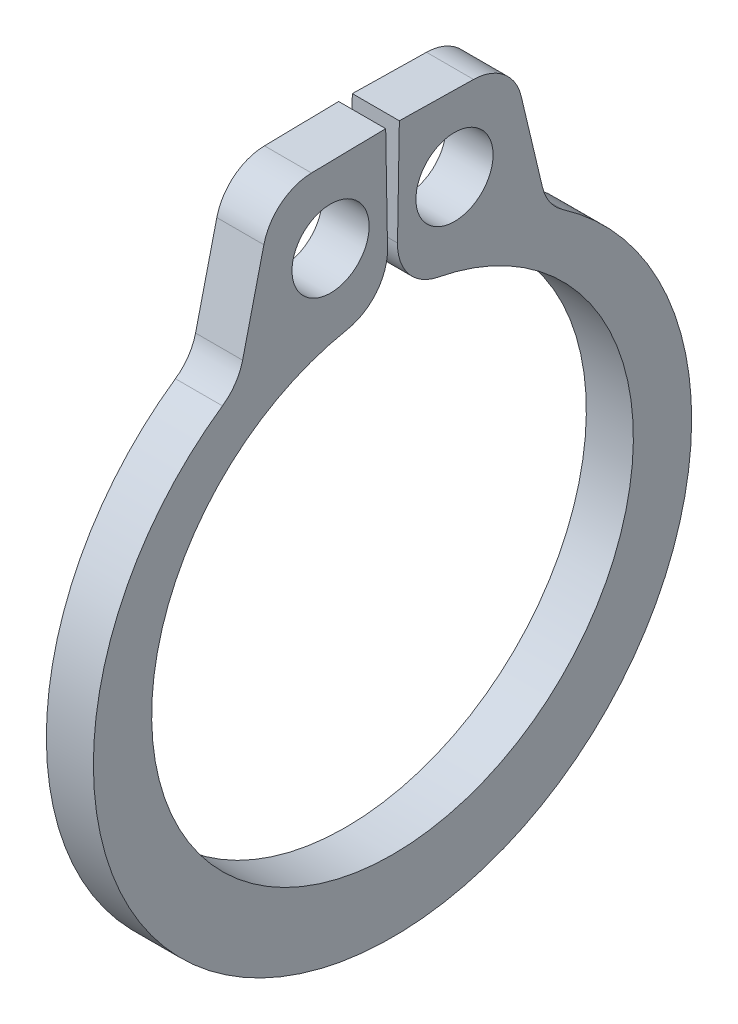
SolidWorks part; units mm, degrees
material "Cast Carbon Steel"
ref_plane "Front" through (0, 0, 0) normal (0, 0, 1) x (1, 0, 0)
ref_plane "Top" through (0, 0, 0) normal (0, 1, 0) x (1, 0, 0)
ref_plane "Right" through (0, 0, 0) normal (1, 0, 0) x (0, 0, -1)
sketch "Sketch1" plane through (0, 0, 0) normal (1, 0, 0) x (0, 0, -1)
  line L0 (0, 0) -> (0, 3.2512) construction
  line L1 (-0.0567, 3.2507) -> (-0.0922, 5.2824)
  line L2 (0.0922, 5.2824) -> (1.616, 5.2558)
  line L3 (1.616, 5.2558) -> (2.086, 3.2789)
  line L4 (0.0567, 3.2507) -> (0.0922, 5.2824)
  line L5 (-0.0922, 5.2824) -> (-1.616, 5.2558)
  line L6 (-1.616, 5.2558) -> (-2.086, 3.2789)
  line L7 (-2.086, 3.2789) -> (-1.7451, 2.7431) construction
  line L8 (2.086, 3.2789) -> (1.7451, 2.7431) construction
  line L9 (0, -3.2512) -> (0, -4.2164) construction
  line L10 (-1.616, 5.2558) -> (-0.0567, 3.2507) construction
  line L11 (0, 3.2512) -> (0, 5.2832) construction
  line L12 (-3.2512, 0) -> (3.2512, 0) construction
  circle A0 centre (0, 0) radius 3.2512 construction
  arc A1 (-0.0567, 3.2507) -> (0.0567, 3.2507) centre (0, 0) ccw
  circle A4 centre (-0.8364, 4.2533) radius 0.5207
  circle A5 centre (0.8364, 4.2533) radius 0.5207
  arc A6 (-2.086, 3.2789) -> (2.086, 3.2789) centre (0, -0.1785) ccw construction
  point P0 (0, -4.2164)
  dimension "Ring ID" = 6.5024
  dimension "Hole Diameter" = 1.0414
  dimension "Min. Sec." = 0.635
  dimension "Max. Sec." = 0.9652
  dimension "Lug Height" = 2.032
  dimension "D2" = 1.524
  dimension "Angle" = 1
sketch "Sketch2" plane through (0, 0, 0) normal (0, 1, 0) x (1, 0, 0)
  line L0 (-0.3175, -4.034) -> (0.3175, -4.034) construction
  line L1 (0, -4.0379) -> (0, 4.0379) construction
  point P8 (0, -4.034)
  dimension "Ring Thickness" = 0.635
sketch "Sketch3" plane through (0, 0, 0) normal (1, 0, 0) x (0, 0, -1)
  line L0 (-1.616, 5.2558) -> (-2.086, 3.2789) construction
  line L1 (-1.616, 5.2558) -> (-2.086, 3.2789)
  line L2 (-0.0922, 5.2824) -> (-1.616, 5.2558) construction
  line L3 (-0.0922, 5.2824) -> (-1.616, 5.2558)
  line L4 (-0.0567, 3.2507) -> (-0.0922, 5.2824) construction
  line L5 (-0.0567, 3.2507) -> (-0.0922, 5.2824)
  line L6 (0.0567, 3.2507) -> (0.0922, 5.2824) construction
  line L7 (0.0567, 3.2507) -> (0.0922, 5.2824)
  line L8 (0.0922, 5.2824) -> (1.616, 5.2558) construction
  line L9 (0.0922, 5.2824) -> (1.616, 5.2558)
  line L10 (1.616, 5.2558) -> (2.086, 3.2789) construction
  line L11 (1.616, 5.2558) -> (2.086, 3.2789)
  arc A0 (-2.086, 3.2789) -> (2.086, 3.2789) centre (0, -0.1785) ccw construction
  arc A1 (-2.086, 3.2789) -> (2.086, 3.2789) centre (0, -0.1785) ccw
  arc A2 (-0.0567, 3.2507) -> (0.0567, 3.2507) centre (0, 0) ccw construction
  arc A3 (-0.0567, 3.2507) -> (0.0567, 3.2507) centre (0, 0) ccw
  circle A4 centre (-0.8364, 4.2533) radius 0.5207 construction
  circle A5 centre (-0.8364, 4.2533) radius 0.5207
  circle A6 centre (0.8364, 4.2533) radius 0.5207 construction
  circle A7 centre (0.8364, 4.2533) radius 0.5207
extrude "Boss-Extrude1" add sketch "Sketch3" along normal up to vertex (0.3175 mm away) and the other way up to vertex (0.3175 mm away) up to point (0.3175, 0, 4.034) other way up to point (-0.3175, 0, 4.034)
fillet "Fillet1" radius 0.6731 6 edges at (0, 3.2789, -2.086) (0, 5.2558, -1.616) (0, 3.2507, -0.0567) (0, 3.2507, 0.0567) (0, 5.2558, 1.616) (0, 3.2789, 2.086)
sketch "Sketch4" plane through (0, 0, 0) normal (1, 0, 0) x (0, 0, -1)
  line L0 (-2.8156, 1.6256) -> (0, 0) construction
  line L1 (0, 0) -> (0, 3.2512) construction
  line L2 (0, 5.2832) -> (0, 3.2512) construction
  arc A0 (-0.0567, 3.2507) -> (0.0567, 3.2507) centre (0, 0) ccw construction
  point P0 (0, 0)
  point P1 (-2.8156, 1.6256)
  dimension "D1" = 60
equation "\"D2@Sketch1\" = \"Lug Height@Sketch1\" * .75"
